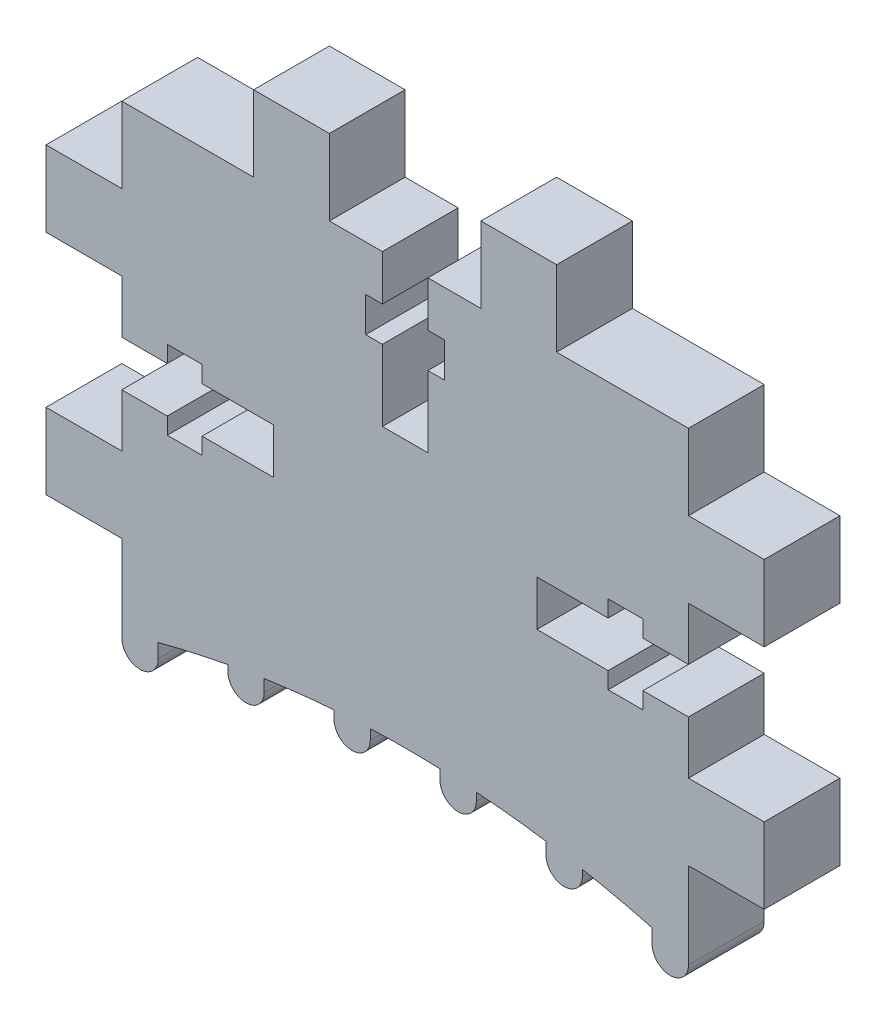
SolidWorks part; units mm, degrees
ref_plane "Front Plane" through (0, 0, 0) normal (0, 0, 1) x (1, 0, 0)
ref_plane "Top Plane" through (0, 0, 0) normal (0, 1, 0) x (1, 0, 0)
ref_plane "Right Plane" through (0, 0, 0) normal (1, 0, 0) x (0, 0, -1)
sketch "Sketch1" plane through (0, 0, 0) normal (0, 0, 1) x (1, 0, 0)
  line L0 (-24.5, 0) -> (45, 0) construction
  line L1 (-21, 11.427) -> (-21, 8.2) construction
  line L2 (-21, 8.2) -> (-15.8, 8.2) construction
  line L3 (-15.8, 8.2) -> (-15.8, 3.5) construction
  line L4 (-15.8, 3.5) -> (15.8, 3.5) construction
  line L5 (15.8, 3.5) -> (15.8, 8.2) construction
  line L6 (15.8, 8.2) -> (21, 8.2) construction
  line L7 (21, 8.2) -> (21, 11.427) construction
  line L8 (0, 0) -> (0, 42.6224) construction
  line L9 (-15.8, 8.2) -> (-15.8, 6.2) construction
  line L10 (-15.8, 6.2) -> (-15.6, 6.2) construction
  line L11 (-15.6, 6.2) -> (-15.6, 3.5) construction
  line L12 (-15.6, 3.5) -> (15.6, 3.5) construction
  line L13 (15.6, 3.5) -> (15.6, 6.2) construction
  line L14 (15.6, 6.2) -> (15.8, 6.2) construction
  line L15 (15.8, 6.2) -> (15.8, 8.2) construction
  line L16 (-17.5, 22.912) -> (-17.5, 13.9522) construction
  line L17 (-10.5, 15.2614) -> (-10.5, 22.912) construction
  line L18 (-3.5, 22.912) -> (-3.5, 16.0251) construction
  line L19 (3.5, 22.912) -> (3.5, 16.3775) construction
  line L20 (10.5, 16.3775) -> (10.5, 22.912) construction
  line L21 (17.5, 22.912) -> (17.5, 14.2835) construction
  line L22 (-24.5, 22.912) -> (-24.5, 12.1189) construction
  line L23 (24.5, 12.1189) -> (24.5, 22.912) construction
  line L24 (24.5, 22.912) -> (17.5, 22.912) construction
  line L25 (3.5, 22.912) -> (-3.5, 22.912) construction
  line L26 (-3.5, 22.912) -> (-10.5, 22.912) construction
  line L27 (-10.5, 22.912) -> (-17.5, 22.912) construction
  line L28 (-17.5, 22.912) -> (-24.5, 22.912) construction
  line L29 (3.5, 22.912) -> (10.5, 22.912) construction
  line L30 (10.5, 22.912) -> (17.5, 22.912) construction
  line L31 (-18.7, 12.1841) -> (-18.7, 11.941) construction
  line L32 (-18.7, 11.941) -> (-16.3, 11.941) construction
  line L33 (-16.3, 11.941) -> (-16.3, 12.8723) construction
  line L34 (-11.7, 13.9128) -> (-11.7, 13.5259) construction
  line L35 (-11.7, 13.5259) -> (-9.3, 13.5259) construction
  line L36 (-9.3, 13.5259) -> (-9.3, 14.3153) construction
  line L37 (-4.7, 14.8258) -> (-4.7, 14.3035) construction
  line L38 (-4.7, 14.3035) -> (-2.3, 14.3035) construction
  line L39 (-2.3, 14.3035) -> (-2.3, 14.9583) construction
  line L40 (2.3, 14.9583) -> (2.3, 14.3035) construction
  line L41 (2.3, 14.3035) -> (4.7, 14.3035) construction
  line L42 (4.7, 14.3035) -> (4.7, 14.8258) construction
  line L43 (9.3, 14.3153) -> (9.3, 13.5259) construction
  line L44 (9.3, 13.5259) -> (11.7, 13.5259) construction
  line L45 (11.7, 13.5259) -> (11.7, 13.9128) construction
  line L46 (16.3, 12.8723) -> (16.3, 11.941) construction
  line L47 (16.3, 11.941) -> (18.7, 11.941) construction
  line L48 (18.7, 11.941) -> (18.7, 12.1841) construction
  line L49 (-18.7, 12.1841) -> (-18.7, 11.941)
  line L50 (-16.3, 11.941) -> (-16.3, 12.8723)
  line L51 (-11.7, 13.9128) -> (-11.7, 13.5259)
  line L52 (-9.3, 13.5259) -> (-9.3, 14.3153)
  line L53 (-4.7, 14.8258) -> (-4.7, 14.3035)
  line L54 (-2.3, 14.3035) -> (-2.3, 14.9583)
  line L55 (2.3, 14.9583) -> (2.3, 14.3035)
  line L56 (4.7, 14.3035) -> (4.7, 14.8258)
  line L57 (9.3, 14.3153) -> (9.3, 13.5259)
  line L58 (11.7, 13.5259) -> (11.7, 13.9128)
  line L59 (16.3, 12.8723) -> (16.3, 11.941)
  line L60 (18.7, 11.941) -> (18.7, 12.1841)
  line L61 (-17.5, 11.941) -> (-17.5, 12.541) construction
  line L62 (-10.5, 14.1259) -> (-10.5, 13.5259) construction
  line L63 (-3.5, 14.9035) -> (-3.5, 14.3035) construction
  line L64 (3.5, 14.9035) -> (3.5, 14.3035) construction
  line L65 (10.5, 14.1259) -> (10.5, 13.5259) construction
  line L66 (17.5, 12.541) -> (17.5, 11.941) construction
  line L67 (-18.7, 12.1841) -> (-18.7, 42.6224) construction
  line L68 (-18.7, 42.6224) -> (18.7, 42.6224) construction
  line L69 (18.7, 42.6224) -> (18.7, 12.1841) construction
  line L70 (18.7, 42.6224) -> (18.7, 37.6224)
  line L71 (-18.7, 42.6224) -> (-18.7, 37.6224)
  line L72 (-18.7, 17.6224) -> (-18.7, 12.1841)
  line L73 (18.7, 17.6224) -> (18.7, 12.1841)
  line L74 (18.7, 27.6224) -> (7.4792, 27.6224) construction
  line L75 (18.7, 26.1224) -> (18.7, 22.6224)
  line L76 (23.7, 22.6224) -> (23.7, 17.6224)
  line L77 (23.7, 17.6224) -> (18.7, 17.6224)
  line L78 (23.7, 22.6224) -> (18.7, 22.6224)
  line L79 (18.7, 29.1224) -> (18.7, 32.6224)
  line L80 (18.7, 32.6224) -> (23.7, 32.6224)
  line L81 (23.7, 32.6224) -> (23.7, 37.6224)
  line L82 (23.7, 37.6224) -> (18.7, 37.6224)
  line L83 (-18.7, 27.6224) -> (-7.4792, 27.6224) construction
  line L84 (-18.7, 29.1224) -> (-18.7, 32.6224)
  line L85 (-23.7, 32.6224) -> (-23.7, 37.6224)
  line L86 (-23.7, 37.6224) -> (-18.7, 37.6224)
  line L87 (-23.7, 32.6224) -> (-18.7, 32.6224)
  line L88 (-18.7, 26.1224) -> (-18.7, 22.6224)
  line L89 (-18.7, 22.6224) -> (-23.7, 22.6224)
  line L90 (-23.7, 22.6224) -> (-23.7, 17.6224)
  line L91 (-23.7, 17.6224) -> (-18.7, 17.6224)
  line L92 (18.7, 26.1224) -> (18.7, 29.1224) construction
  line L93 (18.7, 29.1224) -> (15.7, 29.1224)
  line L94 (13.4, 29.1224) -> (13.4, 30.2224)
  line L95 (15.7, 25.0224) -> (13.4, 25.0224)
  line L96 (15.7, 30.2224) -> (15.7, 29.1224)
  line L97 (13.4, 29.1224) -> (8.7, 29.1224)
  line L98 (8.7, 29.1224) -> (8.7, 26.1224)
  line L99 (8.7, 26.1224) -> (13.4, 26.1224)
  line L100 (15.7, 26.1224) -> (15.7, 25.0224)
  line L101 (13.4, 30.2224) -> (15.7, 30.2224)
  line L102 (13.4, 25.0224) -> (13.4, 26.1224)
  line L103 (15.7, 26.1224) -> (18.7, 26.1224)
  line L104 (8.7, 27.6224) -> (18.7, 27.6224) construction
  line L105 (-18.7, 29.1224) -> (-18.7, 26.1224) construction
  line L106 (-18.7, 26.1224) -> (-15.7, 26.1224)
  line L107 (-13.4, 26.1224) -> (-13.4, 25.0224)
  line L108 (-15.7, 30.2224) -> (-13.4, 30.2224)
  line L109 (-15.7, 25.0224) -> (-15.7, 26.1224)
  line L110 (-13.4, 26.1224) -> (-8.7, 26.1224)
  line L111 (-8.7, 26.1224) -> (-8.7, 29.1224)
  line L112 (-8.7, 29.1224) -> (-13.4, 29.1224)
  line L113 (-15.7, 29.1224) -> (-15.7, 30.2224)
  line L114 (-13.4, 25.0224) -> (-15.7, 25.0224)
  line L115 (-13.4, 30.2224) -> (-13.4, 29.1224)
  line L116 (-15.7, 29.1224) -> (-18.7, 29.1224)
  line L117 (-8.7, 27.6224) -> (-18.7, 27.6224) construction
  line L118 (18.7, 42.6224) -> (10, 42.6224)
  line L119 (-10, 42.6224) -> (-18.7, 42.6224)
  line L120 (0, 42.6224) -> (0, 31.4016) construction
  line L121 (1.5, 42.6224) -> (5, 42.6224)
  line L122 (5, 47.6224) -> (10, 47.6224)
  line L123 (10, 47.6224) -> (10, 42.6224)
  line L124 (5, 47.6224) -> (5, 42.6224)
  line L125 (-1.5, 42.6224) -> (-5, 42.6224)
  line L126 (-5, 42.6224) -> (-5, 47.6224)
  line L127 (-5, 47.6224) -> (-10, 47.6224)
  line L128 (-10, 47.6224) -> (-10, 42.6224)
  line L129 (1.5, 42.6224) -> (-1.5, 42.6224) construction
  line L130 (-1.5, 42.6224) -> (-1.5, 39.6224)
  line L131 (-1.5, 37.3224) -> (-2.6, 37.3224)
  line L132 (2.6, 39.6224) -> (2.6, 37.3224)
  line L133 (-2.6, 39.6224) -> (-1.5, 39.6224)
  line L134 (-1.5, 37.3224) -> (-1.5, 32.6224)
  line L135 (-1.5, 32.6224) -> (1.5, 32.6224)
  line L136 (1.5, 32.6224) -> (1.5, 37.3224)
  line L137 (1.5, 39.6224) -> (2.6, 39.6224)
  line L138 (-2.6, 37.3224) -> (-2.6, 39.6224)
  line L139 (2.6, 37.3224) -> (1.5, 37.3224)
  line L140 (1.5, 39.6224) -> (1.5, 42.6224)
  line L141 (0, 32.6224) -> (0, 42.6224) construction
  arc A0 (-21, 11.427) -> (21, 11.427) centre (0, -48.5) cw construction
  arc A1 (-18.7, 11.941) -> (-16.3, 11.941) centre (-17.5, 11.941) ccw
  arc A2 (-21, 11.427) -> (-18.7, 12.1841) centre (0, -48.5) cw construction
  arc A3 (-11.7, 13.5259) -> (-9.3, 13.5259) centre (-10.5, 13.5259) ccw
  arc A4 (-4.7, 14.3035) -> (-2.3, 14.3035) centre (-3.5, 14.3035) ccw
  arc A5 (2.3, 14.3035) -> (4.7, 14.3035) centre (3.5, 14.3035) ccw
  arc A6 (9.3, 13.5259) -> (11.7, 13.5259) centre (10.5, 13.5259) ccw
  arc A7 (16.3, 11.941) -> (18.7, 11.941) centre (17.5, 11.941) ccw
  arc A8 (-16.3, 12.8723) -> (-11.7, 13.9128) centre (0, -48.5) cw
  arc A9 (-9.3, 14.3153) -> (-4.7, 14.8258) centre (0, -48.5) cw
  arc A10 (-2.3, 14.9583) -> (2.3, 14.9583) centre (0, -48.5) cw
  arc A11 (4.7, 14.8258) -> (9.3, 14.3153) centre (0, -48.5) cw
  arc A12 (11.7, 13.9128) -> (16.3, 12.8723) centre (0, -48.5) cw
  arc A13 (18.7, 12.1841) -> (21, 11.427) centre (0, -48.5) cw construction
  point P16 (0, 15)
  point P73 (-10.5, 14.1259)
  point P75 (-3.5, 14.9035)
  point P76 (3.5, 14.9035)
  point P77 (10.5, 14.1259)
  point P78 (17.5, 12.541)
  point P79 (-17.5, 12.541)
  dimension "D5" = 63.5
  dimension "D7" = 0.2
  dimension "D1" = 3.5
  dimension "D2" = 8.2
  dimension "D3" = 5.2
  dimension "D4" = 15
  dimension "D6" = 42
  dimension "D8" = 2
  dimension "D9" = 2.4
  dimension "D10" = 0.6
  dimension "D11" = 11.941
  dimension "D12" = 14.3035
  dimension "D13" = 10
  dimension "D14" = 5
  dimension "D15" = 5
  dimension "D16" = 10
  dimension "D17" = 5
  dimension "D18" = 5
  dimension "D19" = 5.2
  dimension "D20" = 3
  dimension "D21" = 2.3
  dimension "D22" = 3
  dimension "D23" = 10
  dimension "D24" = 5.2
  dimension "D25" = 3
  dimension "D26" = 2.3
  dimension "D27" = 3
  dimension "D28" = 10
  dimension "D29" = 5
  dimension "D30" = 10
  dimension "D31" = 5
  dimension "D32" = 5
  dimension "D33" = 5.2
  dimension "D34" = 3
  dimension "D35" = 2.3
  dimension "D36" = 3
  dimension "D37" = 10
extrude "Boss-Extrude1" add sketch "Sketch1" along normal blind 5
